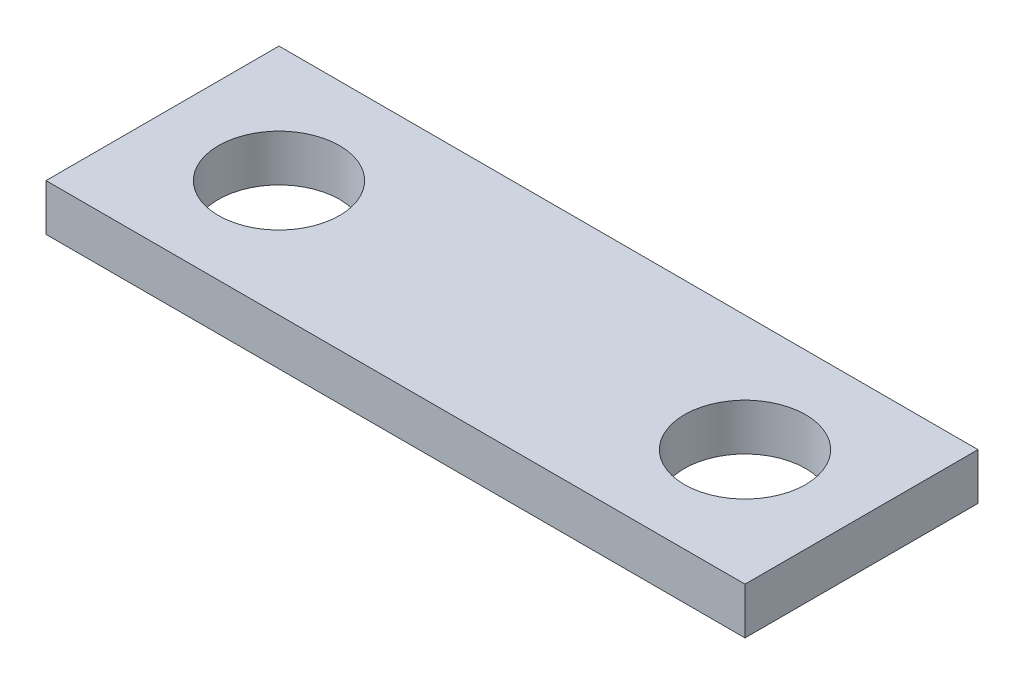
SolidWorks part; units mm, degrees
ref_plane "前视基准面" through (0, 0, 0) normal (0, 0, 1) x (1, 0, 0)
ref_plane "上视基准面" through (0, 0, 0) normal (0, 1, 0) x (1, 0, 0)
ref_plane "右视基准面" through (0, 0, 0) normal (1, 0, 0) x (0, 0, -1)
other "Configuration Table"
sketch "草图1" plane through (0, 0, 0) normal (0, 1, 0) x (1, 0, 0)
  line L1 (-15, -5) -> (15, -5)
  line L2 (-15, -5) -> (-15, 5)
  line L3 (-15, 5) -> (15, 5)
  line L4 (15, -5) -> (15, 5)
  line L5 (-15, -5) -> (15, 5) construction
  line L6 (-15, 5) -> (15, -5) construction
  line L7 (-10, -2.5) -> (10, -2.5)
  line L8 (-10, -2.5) -> (-10, 2.5)
  line L9 (-10, 2.5) -> (10, 2.5)
  line L10 (10, -2.5) -> (10, 2.5)
  line L11 (-10, -2.5) -> (10, 2.5) construction
  line L12 (-10, 2.5) -> (10, -2.5) construction
  circle A0 centre (-10, 0) radius 2.5
  circle A1 centre (10, 0) radius 2.5
  point P0 (0, 0)
  point P6 (0, 0)
  dimension "D5" = 5
  dimension "D1" = 30
  dimension "D2" = 10
  dimension "D3" = 20
  dimension "D4" = 5
extrude "凸台-拉伸1" add sketch "草图1" along normal blind 2 contours L1 L4 L3 L2 A1 L7 A0 L9 | A1 L9 A0 L7
sketch "草图2" plane through (0, 0, 0) normal (0, -1, 0) x (1, 0, 0)
  circle A1 centre (-10, 0) radius 2.6
  circle A2 centre (10, 0) radius 2.6
  dimension "D1" = 5.2
  dimension "D2" = 5.2
extrude "切除-拉伸1" cut sketch "草图2" against normal blind 10
